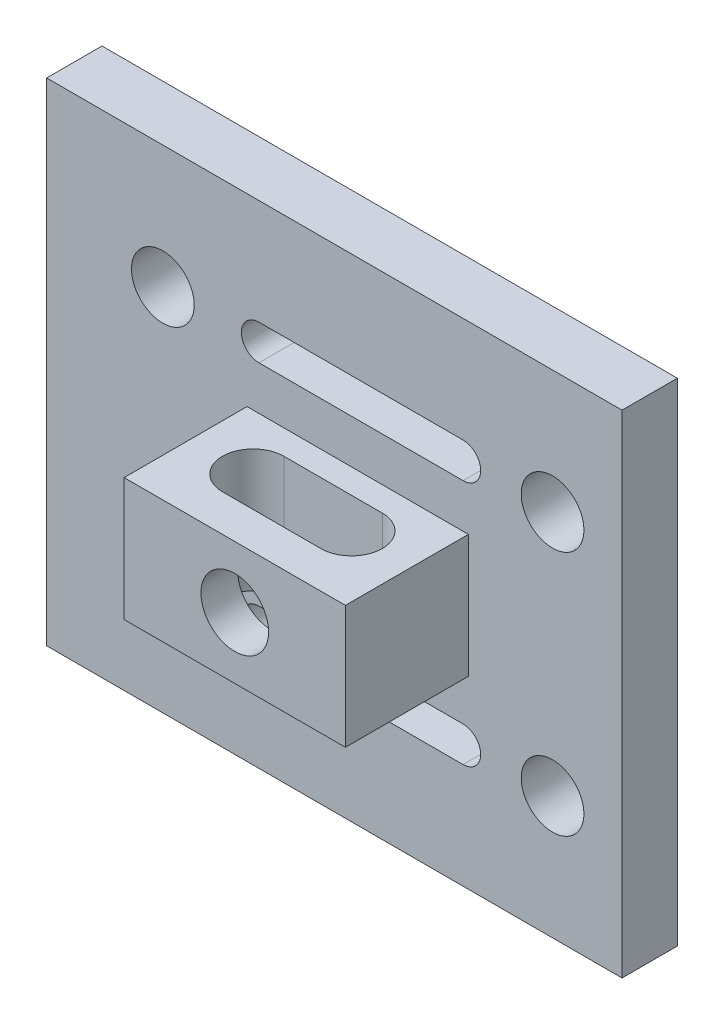
SolidWorks part; units mm, degrees
ref_plane "前视基准面" through (0, 0, 0) normal (0, 0, 1) x (1, 0, 0)
ref_plane "上视基准面" through (0, 0, 0) normal (0, 1, 0) x (1, 0, 0)
ref_plane "右视基准面" through (0, 0, 0) normal (1, 0, 0) x (0, 0, -1)
sketch "草图1" plane through (0, 0, 0) normal (0, 0, 1) x (1, 0, 0)
  line L0 (-25.3, 10) -> (21.5, 10)
  line L1 (21.5, 10) -> (21.5, -10)
  line L2 (21.5, -10) -> (-25.3, -10)
  line L4 (25.3, 0) -> (-25.3, 0) construction
  line L5 (0, -18.0457) -> (0, 18.0457) construction
  line L7 (-25.3, 10) -> (-25.3, -10)
  circle A0 centre (-15.85, 0) radius 2.55
  circle A1 centre (15.85, 0) radius 2.55
  point P12 (0, 0)
  point P15 (0, 0)
  dimension "D1" = 5.1
  dimension "D2" = 5.1
  dimension "D3" = 15.85
  dimension "D4" = 15.85
  dimension "D6" = 21.5
extrude "凸台-拉伸1" add sketch "草图1" along normal blind 4.5
sketch "草图7" plane through (0, 0, 4.5) normal (0, 0, 1) x (1, 0, 0)
  line L0 (-25.3, -10) -> (21.5, -10) construction
  line L1 (-13.32, -10) -> (-10.32, -10)
  line L2 (-10.32, -10) -> (-10.32, -20)
  line L3 (-10.32, -20) -> (-13.32, -20)
  line L4 (-13.32, -20) -> (-13.32, -10)
  line L6 (10.18, -10) -> (10.18, -20)
  line L7 (13.18, -10) -> (10.18, -10)
  line L8 (13.18, -20) -> (13.18, -10)
  line L9 (10.18, -20) -> (13.18, -20)
  circle A0 centre (-15.85, 0) radius 2.55 construction
  dimension "D1" = 2.53
  dimension "D2" = 3
  dimension "D3" = 10
  dimension "D4" = 20.5
sketch "草图8" plane through (0, 0, 0) normal (0, 0, -1) x (-1, 0, 0)
  line L0 (-8.5725, 0) -> (8.0303, 0) construction
  line L1 (-8.5725, 1.4304) -> (8.0303, 1.4304)
  line L2 (-8.5725, -1.4304) -> (8.0303, -1.4304)
  arc A0 (-8.5725, 1.4304) -> (-8.5725, -1.4304) centre (-8.5725, 0) ccw
  arc A1 (8.0303, -1.4304) -> (8.0303, 1.4304) centre (8.0303, 0) ccw
  point P3 (-0.2711, 0)
extrude "切除-拉伸1" cut sketch "草图8" against normal blind 8
ref_plane "基准面1" through (0, 10, 0) normal (0, 1, 0) x (1, 0, 0)
mirror "镜向1" about plane through (0, 10, 0) normal (0, 1, 0) of "凸台-拉伸1"
mirror "镜向3" about plane through (0, 10, 0) normal (0, 1, 0) of "切除-拉伸1"
sketch "草图9" plane through (0, 0, 4.5) normal (0, 0, 1) x (1, 0, 0)
  line L0 (55, 10) -> (-55, 10) construction
  line L1 (-9, 5) -> (9, 5)
  line L2 (-9, 5) -> (-9, 15)
  line L3 (-9, 15) -> (9, 15)
  line L4 (9, 5) -> (9, 15)
  line L5 (-9, 5) -> (9, 15) construction
  line L6 (-9, 15) -> (9, 5) construction
  point P0 (0, 10)
  dimension "D1" = 10
  dimension "D2" = 18
extrude "凸台-拉伸2" add sketch "草图9" along normal blind 10
sketch "草图11" plane through (0, 5, 0) normal (0, -1, 0) x (1, 0, 0)
  line L0 (-4, 9) -> (4, 9) construction
  line L1 (-4, 11.5) -> (4, 11.5)
  line L2 (-4, 6.5) -> (4, 6.5)
  line L3 (9, 14.5) -> (9, 4.5) construction
  line L4 (-9, 14.5) -> (9, 14.5) construction
  arc A0 (-4, 11.5) -> (-4, 6.5) centre (-4, 9) ccw
  arc A1 (4, 6.5) -> (4, 11.5) centre (4, 9) ccw
  point P2 (0, 9)
  dimension "D1" = 5
  dimension "D2" = 4
  dimension "D3" = 9
  dimension "D4" = 3
extrude "切除-拉伸3" cut sketch "草图11" against normal blind 10
sketch "草图12" plane through (0, 0, 14.5) normal (0, 0, 1) x (1, 0, 0)
  line L0 (55, 10) -> (-55, 10) construction
  circle A0 centre (0, 10) radius 2.75
  dimension "D1" = 5.5
extrude "切除-拉伸4" cut sketch "草图12" against normal blind 3
